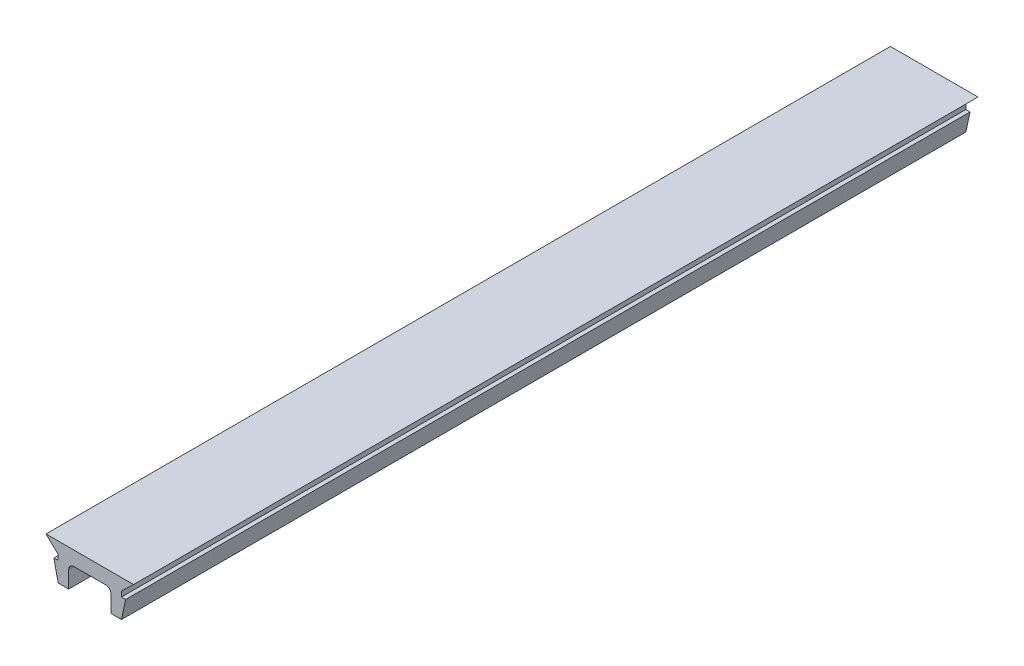
SolidWorks part; units mm, degrees
ref_plane "Front Plane" through (0, 0, 0) normal (0, 0, 1) x (1, 0, 0)
ref_plane "Top Plane" through (0, 0, 0) normal (0, 1, 0) x (1, 0, 0)
ref_plane "Right Plane" through (0, 0, 0) normal (1, 0, 0) x (0, 0, -1)
sketch "Sketch1" plane through (0, 0, 0) normal (0, 0, 1) x (1, 0, 0)
  line L0 (6, 0) -> (6.4, 1.85)
  line L1 (0, 0) -> (1, 0)
  line L2 (0, 1.85) -> (0, 2.35)
  line L3 (0, 3.45) -> (6, 3.45)
  line L4 (6, 1.85) -> (6, 2.35)
  line L5 (6.4, 1.85) -> (6, 1.85)
  line L6 (-0.4, 1.85) -> (0, 0)
  line L7 (0, 1.85) -> (-0.4, 1.85)
  line L8 (5, 0) -> (6, 0)
  line L10 (1, 0) -> (1, 1.6)
  line L11 (1.5, 2.1) -> (4.5, 2.1)
  line L12 (5, 0) -> (5, 1.6)
  line L13 (6, 3.45) -> (7.15, 3.45)
  line L14 (7.15, 3.45) -> (6, 2.35)
  line L16 (0, 2.35) -> (-1.15, 3.45)
  line L17 (-1.15, 3.45) -> (0, 3.45)
  arc A0 (4.5, 2.1) -> (5, 1.6) centre (4.5, 1.6) cw
  arc A1 (1.5, 2.1) -> (1, 1.6) centre (1.5, 1.6) ccw
  point P21 (0, 0)
  dimension "D9" = 0.5
  dimension "D1" = 6
  dimension "D2" = 1.6
  dimension "D3" = 1.85
  dimension "D4" = 0.4
  dimension "D5" = 0.4
  dimension "D7" = 1
  dimension "D8" = 1
  dimension "D10" = 8.3
  dimension "D11" = 0.5
extrude "Boss-Extrude1" add sketch "Sketch1" along normal blind 80
